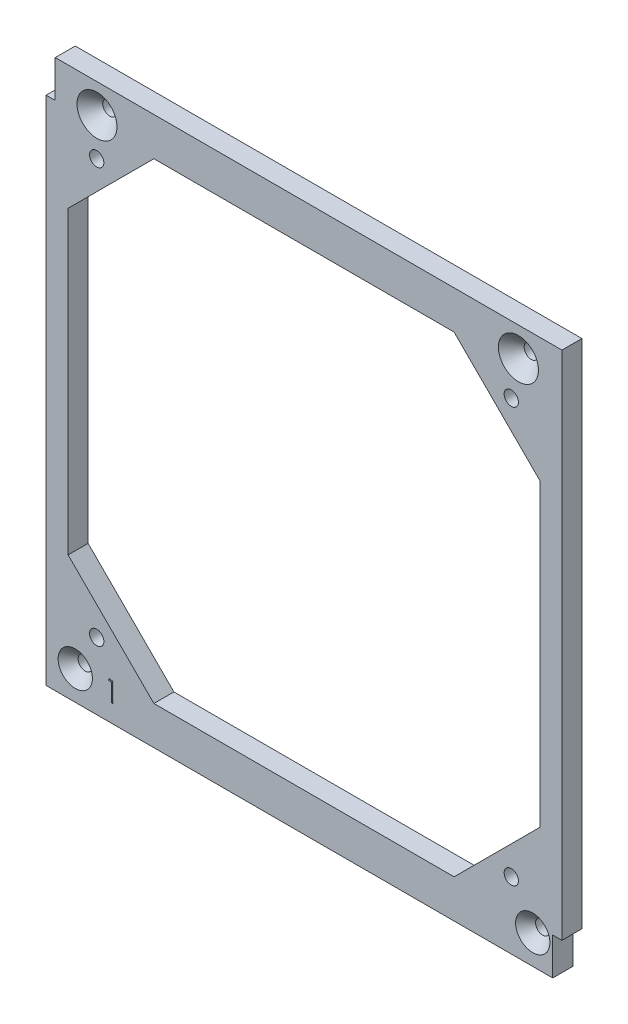
SolidWorks part; units mm, degrees
material "Liga 6061"
ref_plane "Plano frontal" through (0, 0, 0) normal (0, 0, 1) x (1, 0, 0)
ref_plane "Plano superior" through (0, 0, 0) normal (0, 1, 0) x (1, 0, 0)
ref_plane "Plano direito" through (0, 0, 0) normal (1, 0, 0) x (0, 0, -1)
sketch "Esboço1" plane through (0, 0, 0) normal (0, 0, 1) x (1, 0, 0)
  line L1 (-45.1, 47.95) -> (45.1, 47.95)
  line L2 (-45.1, 47.95) -> (-45.1, -47.95)
  line L3 (-45.1, -47.95) -> (45.1, -47.95)
  line L4 (45.1, 47.95) -> (45.1, -47.95)
  point P0 (0, 0)
  dimension "D1" = 90.2
  dimension "D2" = 95.9
sketch "Esboço2" plane through (0, 0, 0) normal (0, 0, 1) x (1, 0, 0)
  line L0 (-45.1, 47.95) -> (-45.1, -47.95) construction
  line L5 (-45.1, -47.95) -> (45.1, -47.95) construction
  circle A0 centre (-36.2, 42.85) radius 1.25
  circle A1 centre (37.5, 42.85) radius 1.25
  circle A2 centre (40, -42.85) radius 1.25
  circle A3 centre (-40, -42.85) radius 1.25
  dimension "D2" = 82.6
  dimension "D3" = 5.1
  dimension "D1" = 8.9
  dimension "D4" = 85.1
  dimension "D5" = 5.1
  dimension "D6" = 90.8
  dimension "D7" = 5.1
sketch "Esboço3" plane through (0, 0, 0) normal (0, 0, 1) x (1, 0, 0)
  line L1 (0, -50) -> (0, 0) construction
  line L2 (-50, 50) -> (50, 50) construction
  line L3 (-50, 50) -> (-50, -50) construction
  line L4 (-50, -50) -> (50, -50) construction
  line L5 (50, 50) -> (50, -50) construction
  line L6 (0, 0) -> (50, 0) construction
  line L8 (-26.25, 41.25) -> (26.25, 41.25)
  line L9 (-41.25, 26.25) -> (-41.25, -26.25)
  line L10 (41.25, 26.25) -> (41.25, -26.25)
  line L11 (-26.25, -41.25) -> (26.25, -41.25)
  line L12 (-41.25, 50) -> (-41.25, -50) construction
  line L13 (-50, 41.25) -> (50, 41.25) construction
  line L14 (41.25, 50) -> (41.25, -50) construction
  line L15 (-50, -41.25) -> (50, -41.25) construction
  line L16 (-26.25, 41.25) -> (-41.25, 26.25)
  line L17 (26.25, 41.25) -> (41.25, 26.25)
  line L18 (41.25, -26.25) -> (26.25, -41.25)
  line L19 (-41.25, -26.25) -> (-26.25, -41.25)
  point P16 (-41.25, 41.25)
  point P17 (41.25, 41.25)
  point P18 (-41.25, -41.25)
  point P19 (41.25, -41.25)
  dimension "D1" = 100
  dimension "D2" = 100
  dimension "D3" = 8.75
  dimension "D4" = 8.75
  dimension "D5" = 8.75
  dimension "D6" = 8.75
extrude "Ressalto-extrusão1" add sketch "Esboço1" along normal blind 3.5
extrude "Corte-extrusão1" cut sketch "Esboço2" along normal blind 5
extrude "Corte-extrusão3" cut sketch "Esboço3" along normal blind 5
sketch "Esboço4" plane through (0, 0, 0) normal (0, 0, 1) x (1, 0, 0)
  line L3 (-36.25, 50) -> (-36.25, -50)
  line L4 (-36.25, 50) -> (-36.25, -50) construction
  line L6 (-50, 36.25) -> (50, 36.25)
  line L7 (-50, 36.25) -> (50, 36.25) construction
  line L9 (36.25, 50) -> (36.25, -50)
  line L10 (36.25, 50) -> (36.25, -50) construction
  line L12 (-50, -36.25) -> (50, -36.25)
  line L13 (-50, -36.25) -> (50, -36.25) construction
  circle A0 centre (-36.25, 36.25) radius 1.25
  circle A1 centre (36.25, 36.25) radius 1.25
  circle A2 centre (-36.25, -36.25) radius 1.25
  circle A3 centre (36.25, -36.25) radius 1.25
  dimension "D1" = 13.75
  dimension "D2" = 13.75
  dimension "D3" = 13.75
  dimension "D4" = 13.75
extrude "Corte-extrusão2" cut sketch "Esboço4" along normal blind 10
chamfer "Chanfro4" distance 1.75 angle 45 1 edges at (-38.75, -42.85, 3.5)
chamfer "Chanfro5" distance 1.75 angle 45 1 edges at (41.25, -42.85, 3.5)
chamfer "Chanfro6" distance 2.25 angle 45 1 edges at (-34.95, 42.85, 3.5)
chamfer "Chanfro7" distance 2.25 angle 45 1 edges at (38.75, 42.85, 3.5)
sketch "Esboço5" plane through (0, 0, 3.5) normal (0, 0, 1) x (1, 0, 0)
  text T0 "1"
extrude "Corte-extrusão4" cut sketch "Esboço5" against normal blind 0.2
sketch "Esboço6" plane through (0, 0, 0) normal (0, 0, -1) x (-1, 0, 0)
  text T0 "1"
extrude "Corte-extrusão5" cut sketch "Esboço6" against normal blind 0.2
sketch "Esboço7" plane through (0, 0, 0) normal (0, 0, -1) x (-1, 0, 0)
  line L0 (-43.5, -47.95) -> (-43.5, -41.45)
  line L1 (45.1, -47.95) -> (-45.1, -47.95) construction
  line L2 (-43.5, -41.45) -> (-45.1, -41.45)
  line L3 (-45.1, 47.95) -> (-45.1, -47.95) construction
  line L4 (-45.1, -41.45) -> (-45.1, -47.95)
  line L5 (-45.1, -47.95) -> (-43.5, -47.95)
extrude "Corte-extrusão7" cut sketch "Esboço7" against normal blind 5 and the other way through all
sketch "Esboço8" plane through (0, 0, 3.5) normal (0, 0, 1) x (1, 0, 0)
  line L0 (-43.5, 47.95) -> (-43.5, 41.45)
  line L1 (-45.1, 47.95) -> (45.1, 47.95) construction
  line L2 (-43.5, 41.45) -> (-45.1, 41.45)
  line L3 (-45.1, 47.95) -> (-45.1, -47.95) construction
  line L4 (-45.1, 41.45) -> (-45.1, 47.95)
  line L5 (-45.1, 47.95) -> (-43.5, 47.95)
extrude "Corte-extrusão8" cut sketch "Esboço8" against normal blind 5
